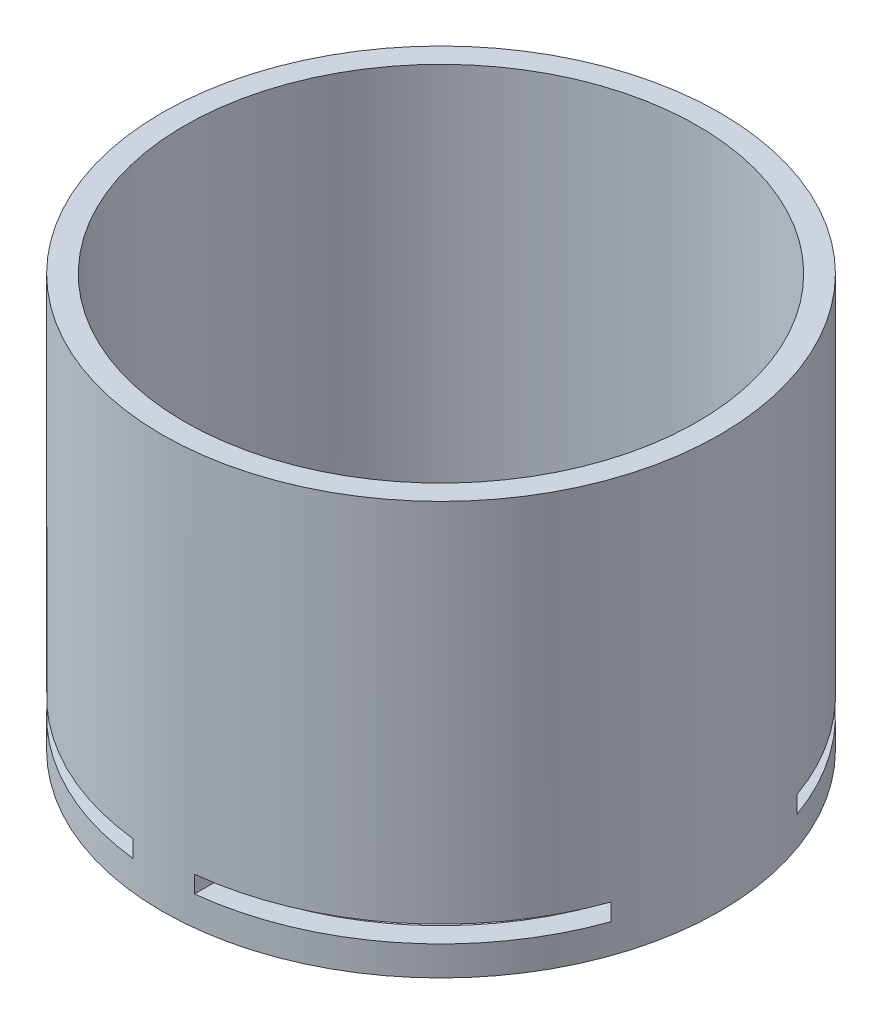
SolidWorks part; units mm, degrees
ref_plane "Front Plane" through (0, 0, 0) normal (0, 0, 1) x (1, 0, 0)
ref_plane "Top Plane" through (0, 0, 0) normal (0, 1, 0) x (1, 0, 0)
ref_plane "Right Plane" through (0, 0, 0) normal (1, 0, 0) x (0, 0, -1)
sketch "Sketch1" plane through (0, 0, 0) normal (0, 1, 0) x (1, 0, 0)
  circle A0 centre (0, 0) radius 60.071
  dimension "D2" = 120.142
extrude "Boss-Extrude1" add sketch "Sketch1" along normal blind 88.9
sketch "Sketch2" plane through (0, 88.9, 0) normal (0, 1, 0) x (1, 0, 0)
  circle A0 centre (0, 0) radius 55.245
  dimension "D1" = 110.49
extrude "Cut-Extrude1" cut sketch "Sketch2" against normal through all
sketch "Sketch6" plane through (0, 0, 0) normal (0, 0, 1) x (1, 0, 0)
  line L0 (-60.071, 88.9) -> (-60.071, 0) construction
  line L1 (-56.642, 10.033) -> (-6.604, 10.033)
  line L2 (-56.642, 10.033) -> (-56.642, 6.35)
  line L3 (-56.642, 6.35) -> (-6.604, 6.35)
  line L7 (-55.245, 0) -> (55.245, 0) construction
  line L8 (-6.604, 10.033) -> (-6.604, 6.35)
  line L9 (0, 0) -> (0, 21.9448) construction
  line L10 (6.604, 10.033) -> (6.604, 6.35)
  line L11 (56.642, 6.35) -> (6.604, 6.35)
  line L12 (56.642, 10.033) -> (6.604, 10.033)
  line L13 (56.642, 10.033) -> (56.642, 6.35)
  dimension "D2" = 3.429
  dimension "D3" = 3.683
  dimension "D4" = 6.35
  dimension "D1" = 6.604
extrude "Cut-Extrude4" cut sketch "Sketch6" against normal through all both and the other way through all
equation "\"tightTol\" = 0.005in"
equation "\"normTol\"= 0.01in"
equation "\"looseTol\"= 0.02in"
equation "\"D2@Sketch6\"=\"normTol\"+0.125000in"
equation "\"D1@Sketch6\"=\"normTol\"+0.250000in"
equation "\"D3@Sketch6\"=\"looseTol\"+0.125000in"
equation "\"D2@Sketch1\"=4.750000in-\"looseTol\""
